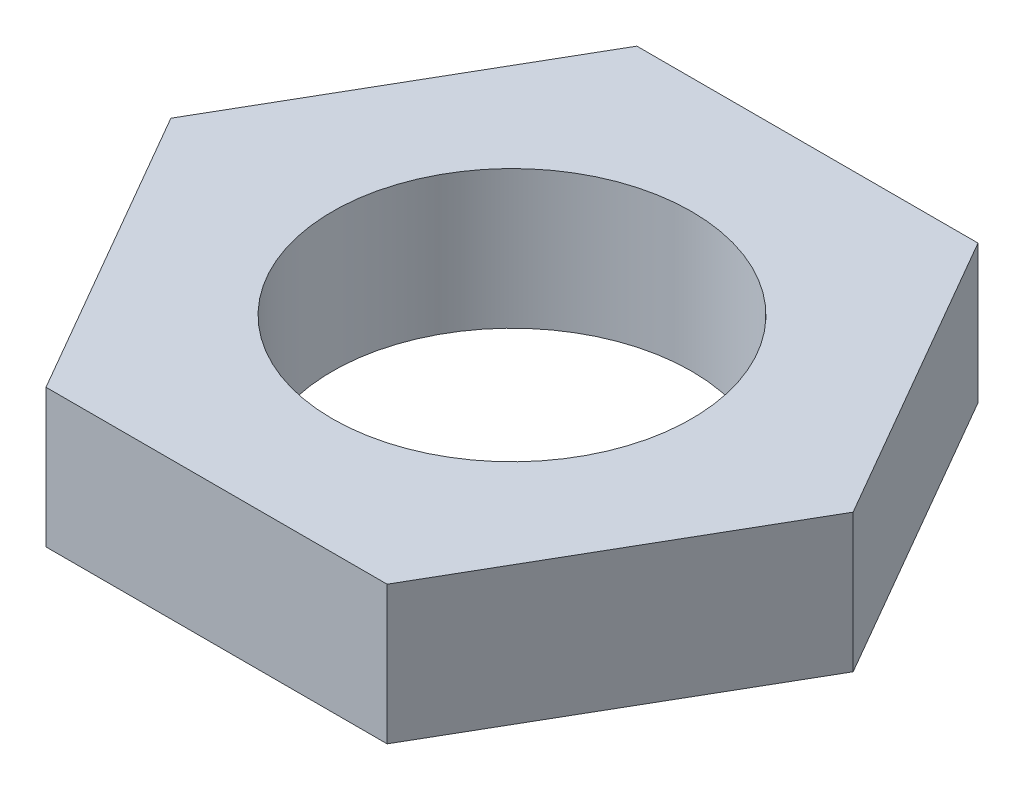
SolidWorks part; units mm, degrees
ref_plane "Front Plane" through (0, 0, 0) normal (0, 0, 1) x (1, 0, 0)
ref_plane "Top Plane" through (0, 0, 0) normal (0, 1, 0) x (1, 0, 0)
ref_plane "Right Plane" through (0, 0, 0) normal (1, 0, 0) x (0, 0, -1)
sketch "Sketch1" plane through (0, 0, 0) normal (0, 1, 0) x (1, 0, 0)
  line L1 (-2.8492, -4.935) -> (2.8492, -4.935)
  line L2 (2.8492, -4.935) -> (5.6984, 0)
  line L3 (5.6984, 0) -> (2.8492, 4.935)
  line L4 (2.8492, 4.935) -> (-2.8492, 4.935)
  line L5 (-2.8492, 4.935) -> (-5.6984, 0)
  line L6 (-5.6984, 0) -> (-2.8492, -4.935)
  circle A0 centre (0, 0) radius 4.935 construction
  circle A1 centre (0, 0) radius 3
  dimension "D2" = 6
  dimension "D1" = 9.87
extrude "Boss-Extrude1" add sketch "Sketch1" along normal blind 2.31
